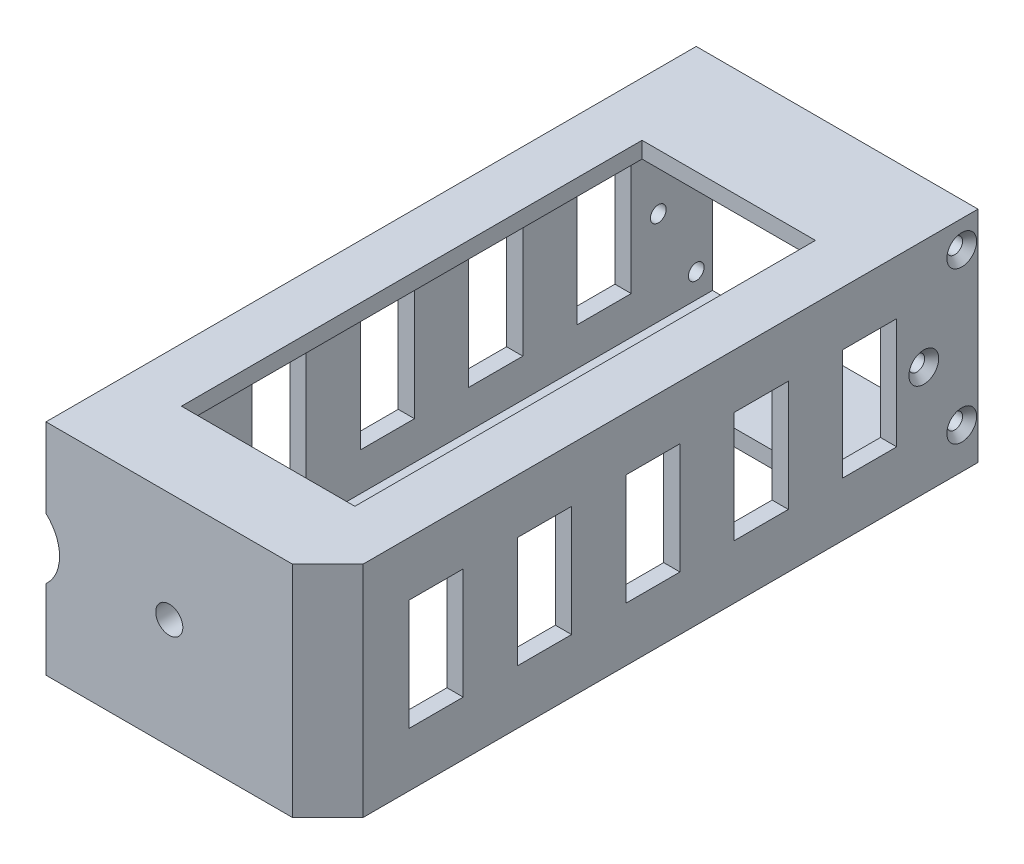
SolidWorks part; units mm, degrees
ref_plane "Plan de face" through (0, 0, 0) normal (0, 0, 1) x (1, 0, 0)
ref_plane "Plan de dessus" through (0, 0, 0) normal (0, 1, 0) x (1, 0, 0)
ref_plane "Plan de droite" through (0, 0, 0) normal (1, 0, 0) x (0, 0, -1)
sketch "Main-Sketch" plane through (0, 0, 0) normal (0, 0, 1) x (1, 0, 0)
  line L1 (-26, -20.25) -> (26, -20.25)
  line L2 (-26, -20.25) -> (-26, 20.25)
  line L3 (-26, 20.25) -> (26, 20.25)
  line L4 (26, -20.25) -> (26, 20.25)
  point P4 (-26, 0)
  point P6 (0, -20.25)
  dimension "D1" = 52
  dimension "D2" = 40.5
extrude "Main-Extrusion" add sketch "Main-Sketch" along normal blind 120
ref_plane "Plan1" through (0, 0, 112) normal (0, 0, 1) x (1, 0, 0)
sketch "Main-Hole-Sketch" plane through (0, 0, 0) normal (0, 0, -1) x (-1, 0, 0)
  line L0 (-26, -20.25) -> (-26, 20.25) construction
  line L1 (-23, 17.25) -> (23, 17.25)
  line L2 (-23, 17.25) -> (-23, -17.25)
  line L3 (-23, -17.25) -> (23, -17.25)
  line L4 (23, 17.25) -> (23, -17.25)
  line L5 (-26, 20.25) -> (26, 20.25) construction
  line L6 (26, 20.25) -> (26, -20.25) construction
  line L7 (26, -20.25) -> (-26, -20.25) construction
  point P4 (-23, 0)
  point P7 (-26, 0)
  point P8 (0, 17.25)
  point P11 (0, 20.25)
  dimension "D1" = 34.5
  dimension "D2" = 46
  dimension "D3" = 3
  dimension "D4" = 3
  dimension "D5" = 3
  dimension "D6" = 3
extrude "Main-Hole" cut sketch "Main-Hole-Sketch" against normal up to surface (112 mm away)
hole_wizard "Fraisage pour vis à tête fraisée M2.51" positions "Esquisse4" profile "Esquisse3" countersink size "M2.5" standard "Ansi Metric" end condition through all
sketch "Esquisse4" plane through (26, 0, 0) normal (1, 0, 0) x (0, 0, -1)
  line L0 (0, -20.25) -> (0, 20.25) construction
  line L1 (-112, 22.275) -> (-112, -22.275) construction
  point P0 (-10, 0)
  point P3 (0, 0)
  dimension "D2" = 102
sketch "Esquisse3" plane through (26, 0, 10) normal (0, 1, 0) x (0, 0, -1)
  line L0 (0, 0) -> (0, 52)
  line L1 (0, 52) -> (1.45, 52)
  line L2 (1.45, 52) -> (1.45, 1.3)
  line L3 (1.45, 1.3) -> (2.75, 0)
  line L5 (2.75, 0) -> (0, 0)
  line L6 (-1.45, 1.3) -> (-2.75, 0) construction
  line L11 (0, -6.35) -> (0, 107.95) construction
  dimension "Diamètre du perçage jusqu'au prochain" = 2.9
  dimension "Profondeur du perçage jusqu'au prochain" = 52
  dimension "Diamètre du fraisage entrant" = 5.5
  dimension "Angle du fraisage entrant" = 90
sketch "Esquisse6" plane through (26, 0, 0) normal (1, 0, 0) x (0, 0, -1)
  line L1 (-105, 10.25) -> (-95, 10.25)
  line L2 (-105, 10.25) -> (-105, -10.25)
  line L3 (-105, -10.25) -> (-95, -10.25)
  line L4 (-95, 10.25) -> (-95, -10.25)
  line L5 (-120, 20.25) -> (0, 20.25) construction
  line L6 (-120, -20.25) -> (0, -20.25) construction
  line L8 (-120, -20.25) -> (-120, 20.25) construction
  dimension "D1" = 10
  dimension "D2" = 10
  dimension "D3" = 10
  dimension "D4" = 15
extrude "Enlèv. mat.-Extru.3" cut sketch "Esquisse6" against normal through all
sketch "Esquisse7" plane through (0, 20.25, 0) normal (0, 1, 0) x (1, 0, 0)
  line L0 (-26, -120) -> (-26, 0) construction
  line L1 (-16, -105) -> (16, -105)
  line L2 (-16, -105) -> (-16, -20)
  line L3 (-16, -20) -> (16, -20)
  line L4 (16, -105) -> (16, -20)
  line L5 (26, -120) -> (26, 0) construction
  line L6 (26, 0) -> (-26, 0) construction
  line L7 (26, -120) -> (-26, -120) construction
  dimension "D1" = 10
  dimension "D2" = 10
  dimension "D3" = 20
  dimension "D4" = 15
extrude "Enlèv. mat.-Extru.4" cut sketch "Esquisse7" against normal through all
pattern_linear "Répétition linéaire1" count 5 spacing 20 along (0, 0, -1) of "Enlèv. mat.-Extru.3"
sketch "Esquisse8" plane through (0, 20.25, 0) normal (0, 1, 0) x (-1, 0, 0)
  line L0 (-19.5, 120) -> (-26, 113.5)
  line L1 (-26, 120) -> (26, 120) construction
  line L2 (-26, 120) -> (-26, 0) construction
  line L3 (-19.5, 120) -> (-26, 120)
  line L4 (-26, 120) -> (-26, 113.5)
  dimension "D1" = 45
  dimension "D2" = 45.5
extrude "Enlèv. mat.-Extru.5" cut sketch "Esquisse8" against normal through all
sketch "Esquisse10" plane through (0, 0, 120) normal (0, 0, 1) x (1, 0, 0)
  line L0 (-26, -20.25) -> (-26, 20.25) construction
  circle A0 centre (-31, 0) radius 7.5
  point P2 (-29.641, 0)
  point P5 (-26, 0)
  dimension "D2" = 15
  dimension "D1" = 5
extrude "Enlèv. mat.-Extru.7" cut sketch "Esquisse10" against normal blind 4
hole_wizard "Fraisage pour vis à tête fraisée M2.52" positions "Esquisse11" profile "Esquisse12" countersink size "M2.5" standard "Ansi Metric" end condition through all
sketch "Esquisse11" plane through (26, 0, 0) normal (1, 0, 0) x (0, 0, -1)
  line L0 (0, -20.25) -> (0, 20.25) construction
  line L1 (-113.5, 20.25) -> (0, 20.25) construction
  point P0 (-3, 15.25)
  dimension "D1" = 3
  dimension "D2" = 5
sketch "Esquisse12" plane through (26, 15.25, 3) normal (0, 1, 0) x (0, 0, -1)
  line L0 (0, 0) -> (0, 52)
  line L1 (0, 52) -> (1.45, 52)
  line L2 (1.45, 52) -> (1.45, 1.3)
  line L3 (1.45, 1.3) -> (2.75, 0)
  line L5 (2.75, 0) -> (0, 0)
  line L6 (-1.45, 1.3) -> (-2.75, 0) construction
  line L11 (0, -6.35) -> (0, 107.95) construction
  dimension "Diamètre du perçage jusqu'au prochain" = 2.9
  dimension "Profondeur du perçage jusqu'au prochain" = 52
  dimension "Diamètre du fraisage entrant" = 5.5
  dimension "Angle du fraisage entrant" = 90
pattern_linear "Répétition linéaire3" count 2 spacing 28 along (0, -1, 0) of "Fraisage pour vis à tête fraisée M2.52"
sketch "Esquisse13" plane through (0, 0, 120) normal (0, 0, 1) x (1, 0, 0)
  line L0 (19.5, 20.25) -> (-26, 20.25) construction
  line L1 (19.5, -20.25) -> (19.5, 20.25) construction
  circle A0 centre (-3.25, 0) radius 2.5
  point P2 (0, 0)
  point P5 (-3.25, 20.25)
  point P8 (19.5, 0)
  dimension "D1" = 5
extrude "Enlèv. mat.-Extru.8" cut sketch "Esquisse13" against normal up to next
